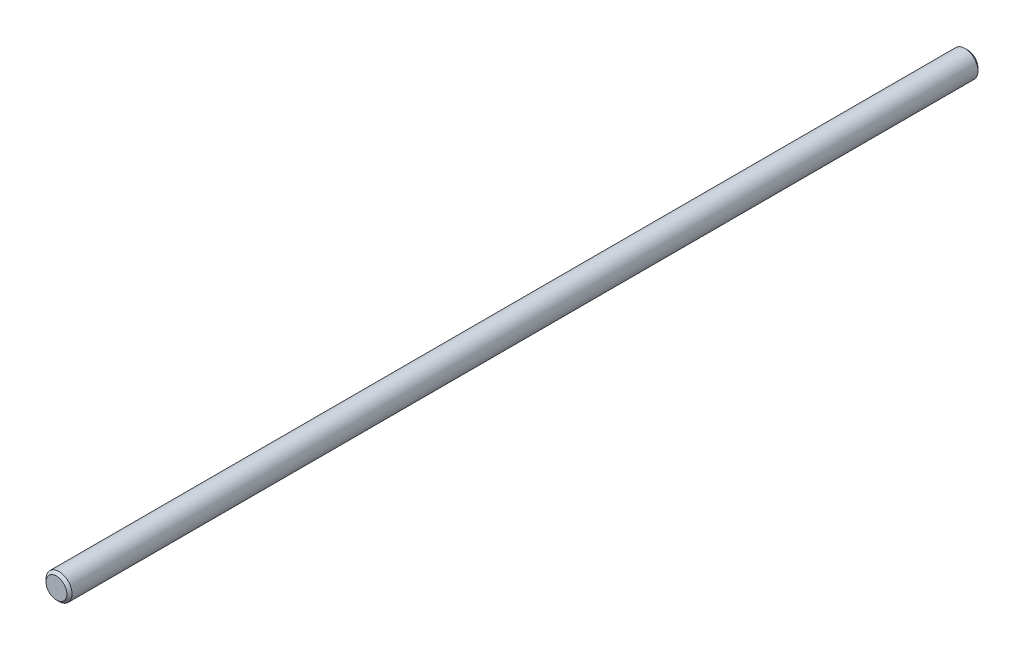
SolidWorks part; units mm, degrees
ref_plane "Piano frontale" through (0, 0, 0) normal (0, 0, 1) x (1, 0, 0)
ref_plane "Piano superiore" through (0, 0, 0) normal (0, 1, 0) x (1, 0, 0)
ref_plane "Piano destro" through (0, 0, 0) normal (1, 0, 0) x (0, 0, -1)
sketch "Schizzo1" plane through (0, 0, 0) normal (0, 0, 1) x (1, 0, 0)
  circle A0 centre (0, 0) radius 5
  dimension "D1" = 10
extrude "Estrusione-Estrusione1" add sketch "Schizzo1" along normal blind 350
chamfer "Smusso1" distance 1 angle 45 2 edges at (5, 0, 350) (5, 0, 0)
